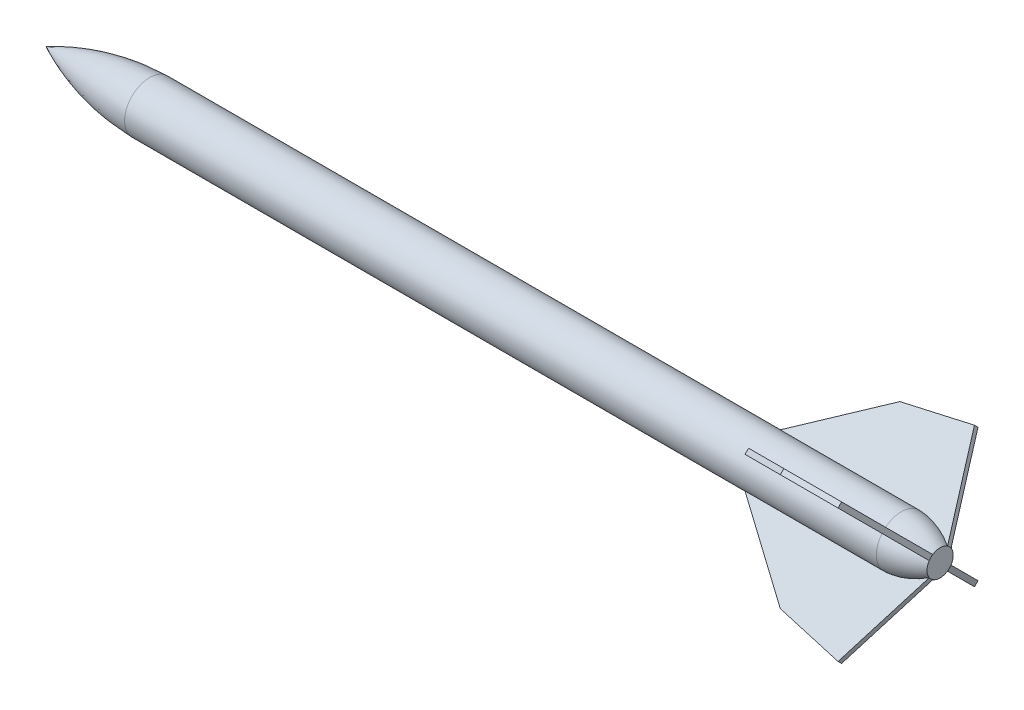
SolidWorks part; units mm, degrees
ref_plane "Спереди" through (0, 0, 0) normal (0, 0, 1) x (1, 0, 0)
ref_plane "Сверху" through (0, 0, 0) normal (0, 1, 0) x (1, 0, 0)
ref_plane "Справа" through (0, 0, 0) normal (1, 0, 0) x (0, 0, -1)
sketch "Эскиз1" plane through (0, 0, 0) normal (1, 0, 0) x (0, 0, -1)
  circle A0 centre (0, 0) radius 50
  circle A1 centre (0, 0) radius 47
  dimension "D1" = 100
  dimension "D2" = 3
extrude "Бобышка-Вытянуть1" add sketch "Эскиз1" along normal blind 1500
sketch "Эскиз2" plane through (0, 0, 0) normal (0, 0, 1) x (1, 0, 0)
  line L0 (-1000, 0) -> (49000, 0) construction
  line L1 (-206.7913, 0) -> (-199.8599, 0)
  line L2 (0.0616, 47.0006) -> (0, 50)
  arc A0 (0, 50) -> (-206.7913, 0) centre (10.1582, -444.6387) ccw
  arc A1 (0.0616, 47.0006) -> (-199.8599, 0) centre (10.1582, -444.6387) ccw
  arc A2 (0.0616, 47.0006) -> (-205.4758, -2.6962) centre (10.1582, -444.6387) ccw construction
  dimension "D1" = 3
revolve "Повернуть1" add sketch "Эскиз2" angle 360 about L0
sketch "Эскиз3" plane through (0, 0, 0) normal (0, 0, 1) x (1, 0, 0)
  line L0 (-1000, 0) -> (49000, 0) construction
  line L1 (1500, 50) -> (0, 50) construction
  line L2 (1574.0668, 28.157) -> (1574.0668, 0)
  line L3 (1500, 50) -> (1500, 47)
  line L4 (1577.0668, 26.1624) -> (1577.0668, 0)
  arc A0 (1500, 50) -> (1605.592, 0) centre (1500, -86.4967) cw
  arc A1 (1500, 47) -> (1603.2713, -1.9011) centre (1500, -86.4967) cw
  dimension "D2" = 3
  dimension "D1" = 3
revolve "Повернуть2" add sketch "Эскиз3" angle 360 about L0
sketch "Эскиз4" plane through (1577.0668, 0, 0) normal (1, 0, 0) x (0, 0, -1)
  line L0 (0, -1000) -> (0, 49000) construction
  line L1 (0, 0) -> (35355.3391, 35355.3391) construction
  line L2 (0, 0) -> (-35355.3391, 35355.3391) construction
  dimension "D1" = 45
ref_plane "Плоскость4" through (0, 0, 0) normal (0, -0.7071, -0.7071) x (-1, 0, 0)
sketch "Эскиз6" plane through (0, 0, 0) normal (0, -0.7071, -0.7071) x (-1, 0, 0)
  line L0 (-1577.0668, 26.1624) -> (-1513.0721, 192.496)
  line L1 (-1513.0721, 192.496) -> (-1381.0538, 168.6594)
  line L2 (-1381.0538, 168.6594) -> (-1226.7701, 50)
  line L3 (0, 50) -> (-1500, 50) construction
  line L4 (-1226.7701, 50) -> (-1500, 50)
  line L5 (-1500, 50) -> (-1500, 0)
  line L6 (-1500, 0) -> (-1577.0668, 0)
  line L7 (-1577.0668, 0) -> (-1577.0668, 26.1624)
  line L8 (-1226.7701, 50) -> (-1226.7701, 0)
  line L9 (-1500, 0) -> (-1226.7701, 0)
extrude "Бобышка-Вытянуть2" add sketch "Эскиз6" along normal mid plane 10 contours L5 L9 L8 L4 | L7 L6 L5 L4 L2 L1 L0
pattern_circular "Круговой массив1" count 4 over 360 about axis through (0, 0.0137, -0.0137) along (1, 0, 0) of "Бобышка-Вытянуть2"
ref_plane "Плоскость5" through (300, 0, 0) normal (1, 0, 0) x (0, 0, -1)
ref_plane "Плоскость6" through (1000, 0, 0) normal (1, 0, 0) x (0, 0, -1)
sketch "Эскиз8" plane through (300, 0, 0) normal (1, 0, 0) x (0, 0, -1)
  line L0 (0, -1000) -> (0, 49000) construction
  line L1 (2, 0) -> (-2, 0)
  line L2 (2, 0) -> (2, -55)
  line L3 (2, -55) -> (-2, -55)
  line L4 (-2, 0) -> (-2, -55)
  line L5 (2, 0) -> (-2, -55) construction
  line L6 (2, -55) -> (-2, 0) construction
  line L7 (-7.5, -53) -> (7.5, -53)
  line L8 (-7.5, -53) -> (-7.5, -57)
  line L9 (-7.5, -57) -> (7.5, -57)
  line L10 (7.5, -53) -> (7.5, -57)
  line L11 (-7.5, -53) -> (7.5, -57) construction
  line L12 (-7.5, -57) -> (7.5, -53) construction
  line L13 (-7.5, -54.3281) -> (-6.1719, -53)
  line L14 (7.5, -54.3281) -> (6.1719, -53)
  point P0 (0, -27.5)
  point P5 (0, -55)
  dimension "D1" = 15
  dimension "D2" = 4
  dimension "D3" = 45
  dimension "D4" = 55
  dimension "D5" = 4
extrude "Бобышка-Вытянуть3" add sketch "Эскиз8" along normal mid plane 20 contours L4 L7 L2 L1 | L7 L4 L3 L2 | L10 L14 L7 L2 L3 L4 L13 L8 L9
sketch "Эскиз9" plane through (1000, 0, 0) normal (1, 0, 0) x (0, 0, -1)
  line L9 (-2, -49.96) -> (-2, -53)
  line L10 (-2, -53) -> (-6.1719, -53)
  line L11 (-6.1719, -53) -> (-7.5, -54.3281)
  line L12 (-7.5, -54.3281) -> (-7.5, -57)
  line L13 (-7.5, -57) -> (7.5, -57)
  line L14 (7.5, -57) -> (7.5, -54.3281)
  line L15 (7.5, -54.3281) -> (6.1719, -53)
  line L16 (6.1719, -53) -> (2, -53)
  line L17 (2, -53) -> (2, -49.96)
  line L18 (-2, -49.96) -> (-2, -53)
  line L19 (-2, -53) -> (-6.1719, -53)
  line L20 (-6.1719, -53) -> (-7.5, -54.3281)
  line L21 (-7.5, -54.3281) -> (-7.5, -57)
  line L22 (-7.5, -57) -> (7.5, -57)
  line L23 (7.5, -57) -> (7.5, -54.3281)
  line L24 (7.5, -54.3281) -> (6.1719, -53)
  line L25 (6.1719, -53) -> (2, -53)
  line L26 (2, -53) -> (2, -49.96)
  arc A1 (-2, -49.96) -> (2, -49.96) centre (0, 0) ccw
  arc A2 (-2, -49.96) -> (2, -49.96) centre (0, 0) ccw
  dimension "D1" = 0
extrude "Бобышка-Вытянуть4" add sketch "Эскиз9" along normal mid plane 20
